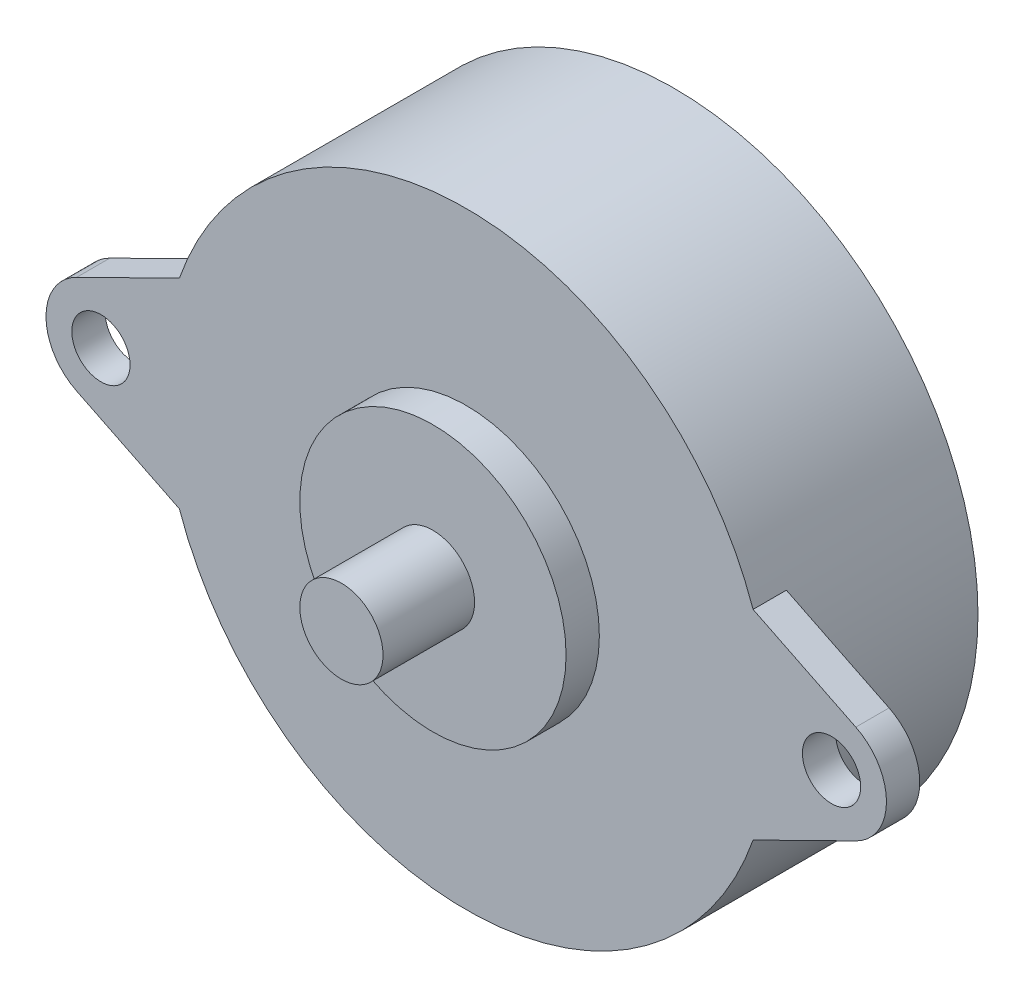
SolidWorks part; units mm, degrees
material "1060 Alloy"
ref_plane "Front Plane" through (0, 0, 0) normal (0, 0, 1) x (1, 0, 0)
ref_plane "Top Plane" through (0, 0, 0) normal (0, 1, 0) x (1, 0, 0)
ref_plane "Right Plane" through (0, 0, 0) normal (1, 0, 0) x (0, 0, -1)
sketch "Sketch1" plane through (0, 0, 0) normal (0, 0, 1) x (1, 0, 0)
  circle A0 centre (0, 0) radius 18.25
  dimension "D1" = 36.5
extrude "Boss-Extrude1" add sketch "Sketch1" along normal blind 12.5
sketch "Sketch2" plane through (0, 0, 12.5) normal (0, 0, 1) x (1, 0, 0)
  line L0 (-21.95, 0) -> (21.95, 0) construction
  line L1 (-23.4079, 2.9605) -> (-17.2355, 6)
  line L2 (-23.4079, -2.9605) -> (-17.2355, -6)
  line L3 (23.4079, 2.9605) -> (17.2355, 6)
  line L4 (23.4079, -2.9605) -> (17.2355, -6)
  circle A0 centre (-21.95, 0) radius 1.75
  circle A1 centre (21.95, 0) radius 1.75
  arc A2 (-23.4079, 2.9605) -> (-23.4079, -2.9605) centre (-21.95, 0) ccw
  arc A3 (23.4079, 2.9605) -> (23.4079, -2.9605) centre (21.95, 0) cw
  circle A4 centre (0, 0) radius 18.25 construction
  arc A5 (-17.2355, 6) -> (-17.2355, -6) centre (0, 0) ccw
  arc A6 (17.2355, 6) -> (17.2355, -6) centre (0, 0) cw
  point P4 (0, 0)
  point P16 (17.4978, 5.1854)
  point P17 (21.95, 3.0803)
  point P19 (17.5721, 4.9279)
  point P20 (16.9762, 6.6987)
  point P21 (0, 0)
  point P22 (0, 0)
  point P23 (0, 0)
  point P24 (0, 0)
  point P25 (0, 0)
  point P26 (-25.25, 0)
  point P27 (25.25, 0)
  point P28 (-18.25, 0)
  dimension "D1" = 3.5
  dimension "D2" = 3.5
  dimension "D3" = 43.9
  dimension "D4" = 50.5
  dimension "D5" = 12
extrude "Boss-Extrude2" add sketch "Sketch2" against normal blind 2
sketch "Sketch3" plane through (0, 0, 12.5) normal (0, 0, 1) x (1, 0, 0)
  circle A0 centre (0, 0) radius 8
  dimension "D1" = 16
extrude "Boss-Extrude3" add sketch "Sketch3" along normal blind 2
sketch "Sketch4" plane through (0, 0, 14.5) normal (0, 0, 1) x (1, 0, 0)
  circle A0 centre (0, 0) radius 2.5
  dimension "D1" = 5
extrude "Boss-Extrude4" add sketch "Sketch4" along normal blind 5.5
